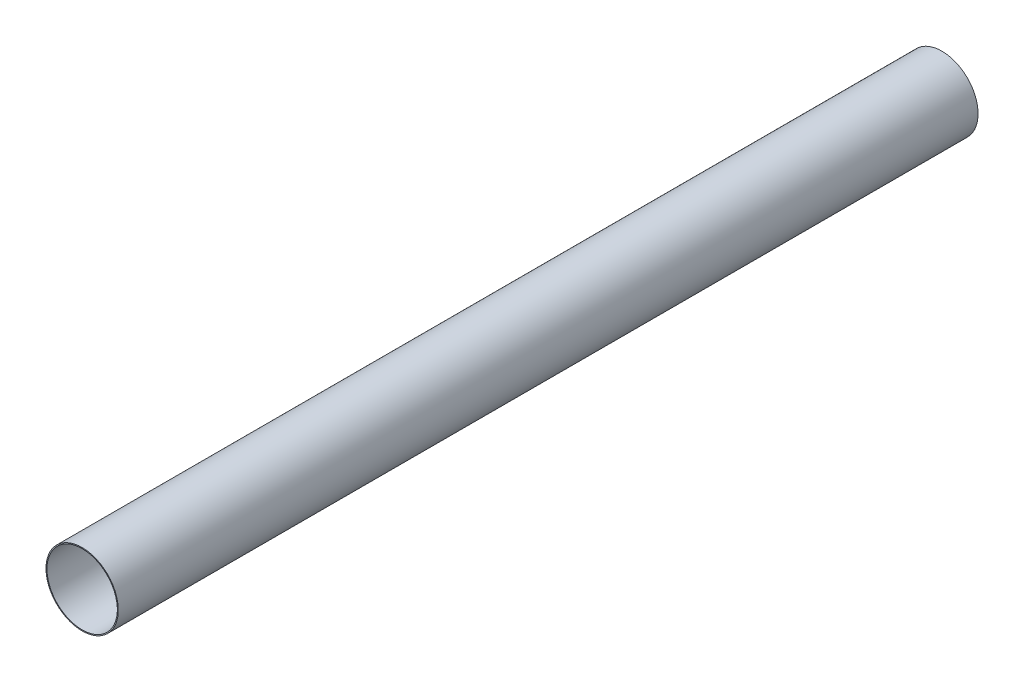
SolidWorks part; units mm, degrees
material "Fibra di Carbonio"
ref_plane "Front Plane" through (0, 0, 0) normal (0, 0, 1) x (1, 0, 0)
ref_plane "Top Plane" through (0, 0, 0) normal (0, 1, 0) x (1, 0, 0)
ref_plane "Right Plane" through (0, 0, 0) normal (1, 0, 0) x (0, 0, -1)
sketch "Sketch1" plane through (0, 0, 0) normal (0, 0, 1) x (1, 0, 0)
  circle A0 centre (0, 0) radius 73
  circle A1 centre (0, 0) radius 75
  dimension "D1" = 150
  dimension "D2" = 2
extrude "Boss-Extrude1" add sketch "Sketch1" along normal blind 1784
